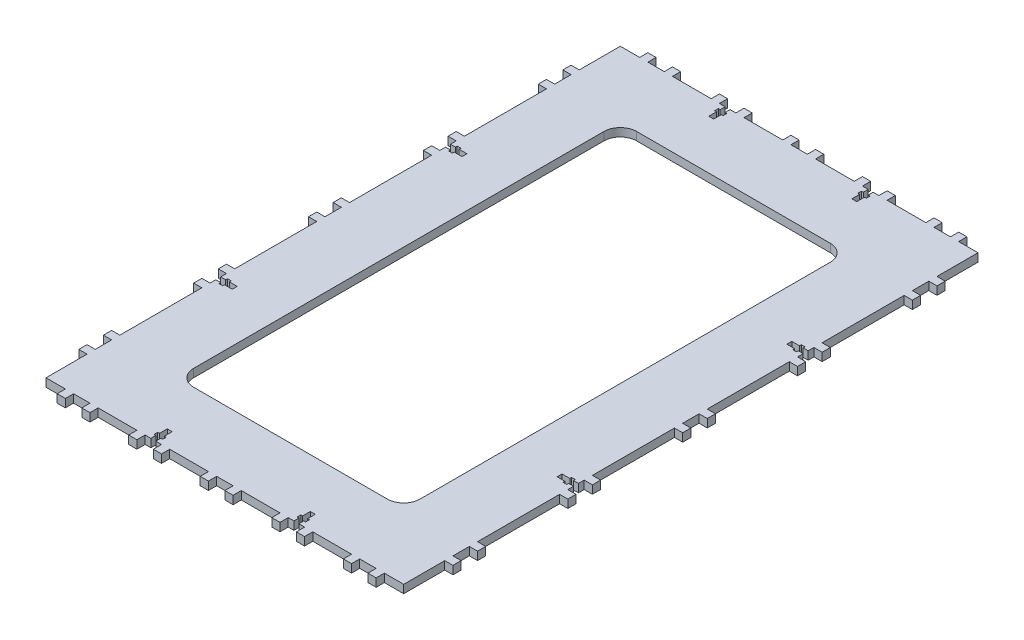
SolidWorks part; units mm, degrees
ref_plane "Front Plane" through (0, 0, 0) normal (0, 0, 1) x (1, 0, 0)
ref_plane "Top Plane" through (0, 0, 0) normal (0, 1, 0) x (1, 0, 0)
ref_plane "Right Plane" through (0, 0, 0) normal (1, 0, 0) x (0, 0, -1)
sketch "Sketch1" plane through (0, 0, 0) normal (0, 1, 0) x (1, 0, 0)
  line L0 (0, 0) -> (0, 175) construction
  line L64 (82.2, -175) -> (92.2, -175)
  line L87 (59, -135) -> (-59, -135)
  line L88 (69, -125) -> (69, 125)
  line L94 (109, -175) -> (109, -150)
  line L96 (-109, -175) -> (-97.2, -175)
  line L97 (-109, -175) -> (-109, -150)
  line L100 (59, 135) -> (-59, 135)
  line L118 (-109, -175) -> (109, 175) construction
  line L119 (-109, 175) -> (109, -175) construction
  line L121 (-109, 175) -> (-97.2, 175)
  line L122 (0, 0) -> (0, -206.09) construction
  line L123 (0, 0) -> (179.3861, 0) construction
  line L124 (0, -175) -> (0, -163.7792) construction
  line L125 (-1.5, -175) -> (-5, -175)
  line L126 (-5, -180) -> (-10, -180)
  line L127 (-10, -180) -> (-10, -175)
  line L128 (-5, -180) -> (-5, -175)
  line L145 (1.5, -175) -> (5, -175)
  line L146 (5, -175) -> (5, -180)
  line L147 (5, -180) -> (10, -180)
  line L148 (10, -180) -> (10, -175)
  line L149 (43.6, -175) -> (43.6, -177.9498) construction
  line L150 (42.1, -175) -> (38.6, -175)
  line L151 (38.6, -180) -> (33.6, -180)
  line L152 (33.6, -180) -> (33.6, -175)
  line L153 (38.6, -180) -> (38.6, -175)
  line L154 (45.1, -175) -> (48.6, -175)
  line L155 (48.6, -175) -> (48.6, -180)
  line L156 (48.6, -180) -> (53.6, -180)
  line L157 (53.6, -180) -> (53.6, -175)
  line L158 (87.2, -175) -> (87.2, -176.7176) construction
  line L159 (102.5, -175) -> (97.2, -175)
  line L160 (82.2, -180) -> (77.2, -180)
  line L161 (77.2, -180) -> (77.2, -175)
  line L162 (82.2, -180) -> (82.2, -175)
  line L163 (71.9, -175) -> (77.2, -175)
  line L164 (92.2, -175) -> (92.2, -180)
  line L165 (92.2, -180) -> (97.2, -180)
  line L166 (97.2, -180) -> (97.2, -175)
  line L167 (42.1, -175) -> (45.1, -175) construction
  line L168 (45.1, -175) -> (45.1, -172)
  line L169 (45.1, -169.7) -> (46.2, -169.7)
  line L170 (41, -172) -> (41, -169.7)
  line L171 (46.2, -172) -> (45.1, -172)
  line L172 (45.1, -169.7) -> (45.1, -165)
  line L173 (45.1, -165) -> (42.1, -165)
  line L174 (42.1, -165) -> (42.1, -169.7)
  line L175 (42.1, -172) -> (41, -172)
  line L176 (46.2, -169.7) -> (46.2, -172)
  line L177 (41, -169.7) -> (42.1, -169.7)
  line L178 (42.1, -172) -> (42.1, -175)
  line L179 (43.6, -165) -> (43.6, -175) construction
  line L180 (-1.5, -175) -> (1.5, -175) construction
  line L181 (109, -140) -> (144.5683, -140) construction
  line L182 (109, -141.5) -> (109, -145)
  line L183 (114, -145) -> (114, -150)
  line L184 (114, -150) -> (109, -150)
  line L185 (114, -145) -> (109, -145)
  line L186 (109, -138.5) -> (109, -135)
  line L187 (109, -135) -> (114, -135)
  line L188 (114, -135) -> (114, -130)
  line L189 (114, -130) -> (109, -130)
  line L190 (109, -141.5) -> (109, -138.5) construction
  line L191 (109, -130) -> (109, -80)
  line L192 (0, -165) -> (0, -175) construction
  line L193 (102.5, -175) -> (97.2, -175) construction
  line L194 (109, -145) -> (109, -135)
  line L195 (109, 10) -> (109, 60)
  line L196 (109, -5) -> (109, 5)
  line L197 (109, -60) -> (109, -10)
  line L198 (109, -75) -> (109, -65)
  line L199 (82.2, -175) -> (92.2, -175)
  line L200 (97.2, -175) -> (109, -175)
  line L201 (38.6, -175) -> (48.6, -175)
  line L202 (53.6, -175) -> (77.2, -175)
  line L203 (-5, -175) -> (5, -175)
  line L204 (10, -175) -> (33.6, -175)
  line L205 (87.2, -165) -> (87.2, -175) construction
  line L206 (109, -70) -> (138.8281, -70) construction
  line L207 (109, -71.5) -> (109, -75)
  line L208 (114, -75) -> (114, -80)
  line L209 (114, -80) -> (109, -80)
  line L210 (114, -75) -> (109, -75)
  line L211 (109, -68.5) -> (109, -65)
  line L212 (109, -65) -> (114, -65)
  line L213 (114, -65) -> (114, -60)
  line L214 (114, -60) -> (109, -60)
  line L215 (109, -71.5) -> (109, -68.5) construction
  line L216 (109, -68.5) -> (106, -68.5)
  line L217 (103.7, -68.5) -> (103.7, -67.4)
  line L218 (106, -72.6) -> (103.7, -72.6)
  line L219 (106, -67.4) -> (106, -68.5)
  line L220 (103.7, -68.5) -> (99, -68.5)
  line L221 (99, -68.5) -> (99, -71.5)
  line L222 (99, -71.5) -> (103.7, -71.5)
  line L223 (106, -71.5) -> (106, -72.6)
  line L224 (103.7, -67.4) -> (106, -67.4)
  line L225 (103.7, -72.6) -> (103.7, -71.5)
  line L226 (106, -71.5) -> (109, -71.5)
  line L227 (99, -70) -> (109, -70) construction
  line L228 (109, 0) -> (144.5683, 0) construction
  line L229 (109, -1.5) -> (109, -5)
  line L230 (114, -5) -> (114, -10)
  line L231 (114, -10) -> (109, -10)
  line L232 (114, -5) -> (109, -5)
  line L233 (109, 1.5) -> (109, 5)
  line L234 (109, 5) -> (114, 5)
  line L235 (114, 5) -> (114, 10)
  line L236 (114, 10) -> (109, 10)
  line L237 (109, -1.5) -> (109, 1.5) construction
  line L238 (99, 70) -> (109, 70) construction
  line L239 (109, 71.5) -> (109, 68.5) construction
  line L240 (109, 70) -> (138.8281, 70) construction
  line L241 (109, 141.5) -> (109, 138.5) construction
  line L242 (109, 140) -> (144.5683, 140) construction
  line L243 (106, 71.5) -> (109, 71.5)
  line L244 (103.7, 72.6) -> (103.7, 71.5)
  line L245 (103.7, 67.4) -> (106, 67.4)
  line L246 (106, 71.5) -> (106, 72.6)
  line L247 (99, 71.5) -> (103.7, 71.5)
  line L248 (99, 68.5) -> (99, 71.5)
  line L249 (120, 0) -> (109, 0) construction
  line L250 (103.7, 68.5) -> (99, 68.5)
  line L251 (106, 67.4) -> (106, 68.5)
  line L252 (106, 72.6) -> (103.7, 72.6)
  line L253 (103.7, 68.5) -> (103.7, 67.4)
  line L254 (109, 68.5) -> (106, 68.5)
  line L255 (114, 60) -> (109, 60)
  line L256 (114, 65) -> (114, 60)
  line L257 (109, 65) -> (114, 65)
  line L258 (109, 68.5) -> (109, 65)
  line L259 (114, 75) -> (109, 75)
  line L260 (114, 80) -> (109, 80)
  line L261 (114, 75) -> (114, 80)
  line L262 (109, 71.5) -> (109, 75)
  line L263 (109, 75) -> (109, 65)
  line L264 (109, 145) -> (109, 135)
  line L265 (114, 130) -> (109, 130)
  line L266 (114, 135) -> (114, 130)
  line L267 (109, 135) -> (114, 135)
  line L268 (109, 138.5) -> (109, 135)
  line L269 (114, 145) -> (109, 145)
  line L270 (114, 150) -> (109, 150)
  line L271 (114, 145) -> (114, 150)
  line L272 (109, 141.5) -> (109, 145)
  line L273 (-120, 0) -> (-109, 0) construction
  line L274 (-109, 140) -> (-144.5683, 140) construction
  line L275 (-109, 141.5) -> (-109, 138.5) construction
  line L276 (-109, 70) -> (-138.8281, 70) construction
  line L277 (-109, 71.5) -> (-109, 68.5) construction
  line L278 (-99, 70) -> (-109, 70) construction
  line L279 (-109, -1.5) -> (-109, 1.5) construction
  line L280 (-109, 0) -> (-144.5683, 0) construction
  line L281 (-99, -70) -> (-109, -70) construction
  line L282 (-109, -71.5) -> (-109, -68.5) construction
  line L283 (-109, -70) -> (-138.8281, -70) construction
  line L284 (-109, -141.5) -> (-109, -138.5) construction
  line L285 (-109, -140) -> (-144.5683, -140) construction
  line L286 (-109, 141.5) -> (-109, 145)
  line L287 (-114, 145) -> (-114, 150)
  line L288 (-114, 150) -> (-109, 150)
  line L289 (-114, 145) -> (-109, 145)
  line L290 (-109, 138.5) -> (-109, 135)
  line L291 (-109, 135) -> (-114, 135)
  line L292 (-114, 135) -> (-114, 130)
  line L293 (-114, 130) -> (-109, 130)
  line L294 (-109, 145) -> (-109, 135)
  line L295 (-109, 75) -> (-109, 65)
  line L296 (-109, 71.5) -> (-109, 75)
  line L297 (-114, 75) -> (-114, 80)
  line L298 (-114, 80) -> (-109, 80)
  line L299 (-114, 75) -> (-109, 75)
  line L300 (-109, 68.5) -> (-109, 65)
  line L301 (-109, 65) -> (-114, 65)
  line L302 (-114, 65) -> (-114, 60)
  line L303 (-114, 60) -> (-109, 60)
  line L304 (-109, 68.5) -> (-106, 68.5)
  line L305 (-103.7, 68.5) -> (-103.7, 67.4)
  line L306 (-106, 72.6) -> (-103.7, 72.6)
  line L307 (-106, 67.4) -> (-106, 68.5)
  line L308 (-103.7, 68.5) -> (-99, 68.5)
  line L309 (-99, 68.5) -> (-99, 71.5)
  line L310 (-99, 71.5) -> (-103.7, 71.5)
  line L311 (-106, 71.5) -> (-106, 72.6)
  line L312 (-103.7, 67.4) -> (-106, 67.4)
  line L313 (-103.7, 72.6) -> (-103.7, 71.5)
  line L314 (-106, 71.5) -> (-109, 71.5)
  line L315 (-114, 10) -> (-109, 10)
  line L316 (-114, 5) -> (-114, 10)
  line L317 (-109, 5) -> (-114, 5)
  line L318 (-109, 1.5) -> (-109, 5)
  line L319 (-114, -5) -> (-109, -5)
  line L320 (-114, -10) -> (-109, -10)
  line L321 (-114, -5) -> (-114, -10)
  line L322 (-109, -1.5) -> (-109, -5)
  line L323 (-106, -71.5) -> (-109, -71.5)
  line L324 (-103.7, -72.6) -> (-103.7, -71.5)
  line L325 (-103.7, -67.4) -> (-106, -67.4)
  line L326 (-106, -71.5) -> (-106, -72.6)
  line L327 (-99, -71.5) -> (-103.7, -71.5)
  line L328 (-99, -68.5) -> (-99, -71.5)
  line L329 (-103.7, -68.5) -> (-99, -68.5)
  line L330 (-106, -67.4) -> (-106, -68.5)
  line L331 (-106, -72.6) -> (-103.7, -72.6)
  line L332 (-103.7, -68.5) -> (-103.7, -67.4)
  line L333 (-109, -68.5) -> (-106, -68.5)
  line L334 (-114, -60) -> (-109, -60)
  line L335 (-114, -65) -> (-114, -60)
  line L336 (-109, -65) -> (-114, -65)
  line L337 (-109, -68.5) -> (-109, -65)
  line L338 (-114, -75) -> (-109, -75)
  line L339 (-114, -80) -> (-109, -80)
  line L340 (-114, -75) -> (-114, -80)
  line L341 (-109, -71.5) -> (-109, -75)
  line L342 (-109, -75) -> (-109, -65)
  line L343 (-109, -5) -> (-109, 5)
  line L344 (-109, -145) -> (-109, -135)
  line L345 (-114, -130) -> (-109, -130)
  line L346 (-114, -135) -> (-114, -130)
  line L347 (-109, -135) -> (-114, -135)
  line L348 (-109, -138.5) -> (-109, -135)
  line L349 (-114, -145) -> (-109, -145)
  line L350 (-114, -150) -> (-109, -150)
  line L351 (-114, -145) -> (-114, -150)
  line L352 (-109, -141.5) -> (-109, -145)
  line L353 (-87.2, -165) -> (-87.2, -175) construction
  line L354 (-102.5, -175) -> (-97.2, -175) construction
  line L355 (-43.6, -165) -> (-43.6, -175) construction
  line L356 (-87.2, -175) -> (-87.2, -176.7176) construction
  line L357 (-42.1, -175) -> (-45.1, -175) construction
  line L358 (-53.6, -175) -> (-77.2, -175)
  line L359 (-43.6, -175) -> (-43.6, -177.9498) construction
  line L360 (-82.2, -175) -> (-92.2, -175)
  line L361 (-38.6, -175) -> (-48.6, -175)
  line L362 (-42.1, -172) -> (-42.1, -175)
  line L363 (-41, -169.7) -> (-42.1, -169.7)
  line L364 (-46.2, -169.7) -> (-46.2, -172)
  line L365 (-42.1, -172) -> (-41, -172)
  line L366 (-42.1, -165) -> (-42.1, -169.7)
  line L367 (-97.2, -180) -> (-97.2, -175)
  line L368 (-92.2, -180) -> (-97.2, -180)
  line L369 (-92.2, -175) -> (-92.2, -180)
  line L370 (-71.9, -175) -> (-77.2, -175)
  line L371 (-82.2, -180) -> (-82.2, -175)
  line L372 (-77.2, -180) -> (-77.2, -175)
  line L373 (-82.2, -180) -> (-77.2, -180)
  line L374 (-102.5, -175) -> (-97.2, -175)
  line L375 (-45.1, -165) -> (-42.1, -165)
  line L376 (-45.1, -169.7) -> (-45.1, -165)
  line L377 (-46.2, -172) -> (-45.1, -172)
  line L378 (-41, -172) -> (-41, -169.7)
  line L379 (-45.1, -169.7) -> (-46.2, -169.7)
  line L380 (-45.1, -175) -> (-45.1, -172)
  line L381 (-53.6, -180) -> (-53.6, -175)
  line L382 (-48.6, -180) -> (-53.6, -180)
  line L383 (-48.6, -175) -> (-48.6, -180)
  line L384 (-45.1, -175) -> (-48.6, -175)
  line L385 (-38.6, -180) -> (-38.6, -175)
  line L386 (-33.6, -180) -> (-33.6, -175)
  line L387 (-38.6, -180) -> (-33.6, -180)
  line L388 (-42.1, -175) -> (-38.6, -175)
  line L389 (-43.6, 175) -> (-43.6, 177.9498) construction
  line L390 (-42.1, 175) -> (-45.1, 175) construction
  line L391 (-87.2, 175) -> (-87.2, 176.7176) construction
  line L392 (-43.6, 165) -> (-43.6, 175) construction
  line L393 (-102.5, 175) -> (-97.2, 175) construction
  line L394 (-87.2, 165) -> (-87.2, 175) construction
  line L395 (87.2, 165) -> (87.2, 175) construction
  line L396 (102.5, 175) -> (97.2, 175) construction
  line L397 (0, 165) -> (0, 175) construction
  line L398 (-1.5, 175) -> (1.5, 175) construction
  line L399 (43.6, 165) -> (43.6, 175) construction
  line L400 (42.1, 175) -> (45.1, 175) construction
  line L401 (87.2, 175) -> (87.2, 176.7176) construction
  line L402 (43.6, 175) -> (43.6, 177.9498) construction
  line L403 (0, 175) -> (0, 163.7792) construction
  line L404 (-42.1, 175) -> (-38.6, 175)
  line L405 (-38.6, 180) -> (-33.6, 180)
  line L406 (-33.6, 180) -> (-33.6, 175)
  line L407 (-38.6, 180) -> (-38.6, 175)
  line L408 (-45.1, 175) -> (-48.6, 175)
  line L409 (-48.6, 175) -> (-48.6, 180)
  line L410 (-48.6, 180) -> (-53.6, 180)
  line L411 (-53.6, 180) -> (-53.6, 175)
  line L412 (-45.1, 175) -> (-45.1, 172)
  line L413 (-45.1, 169.7) -> (-46.2, 169.7)
  line L414 (-41, 172) -> (-41, 169.7)
  line L415 (-46.2, 172) -> (-45.1, 172)
  line L416 (-45.1, 169.7) -> (-45.1, 165)
  line L417 (-45.1, 165) -> (-42.1, 165)
  line L418 (-102.5, 175) -> (-97.2, 175)
  line L419 (-82.2, 180) -> (-77.2, 180)
  line L420 (-77.2, 180) -> (-77.2, 175)
  line L421 (-82.2, 180) -> (-82.2, 175)
  line L422 (-71.9, 175) -> (-77.2, 175)
  line L423 (-92.2, 175) -> (-92.2, 180)
  line L424 (-92.2, 180) -> (-97.2, 180)
  line L425 (-97.2, 180) -> (-97.2, 175)
  line L426 (-42.1, 165) -> (-42.1, 169.7)
  line L427 (-42.1, 172) -> (-41, 172)
  line L428 (-46.2, 169.7) -> (-46.2, 172)
  line L429 (-41, 169.7) -> (-42.1, 169.7)
  line L430 (-42.1, 172) -> (-42.1, 175)
  line L431 (-38.6, 175) -> (-48.6, 175)
  line L432 (-82.2, 175) -> (-92.2, 175)
  line L433 (-53.6, 175) -> (-77.2, 175)
  line L434 (10, 175) -> (33.6, 175)
  line L435 (-5, 175) -> (5, 175)
  line L436 (53.6, 175) -> (77.2, 175)
  line L437 (38.6, 175) -> (48.6, 175)
  line L438 (82.2, 175) -> (92.2, 175)
  line L439 (42.1, 172) -> (42.1, 175)
  line L440 (41, 169.7) -> (42.1, 169.7)
  line L441 (46.2, 169.7) -> (46.2, 172)
  line L442 (42.1, 172) -> (41, 172)
  line L443 (42.1, 165) -> (42.1, 169.7)
  line L444 (45.1, 165) -> (42.1, 165)
  line L445 (45.1, 169.7) -> (45.1, 165)
  line L446 (46.2, 172) -> (45.1, 172)
  line L447 (41, 172) -> (41, 169.7)
  line L448 (45.1, 169.7) -> (46.2, 169.7)
  line L449 (45.1, 175) -> (45.1, 172)
  line L450 (97.2, 180) -> (97.2, 175)
  line L451 (92.2, 180) -> (97.2, 180)
  line L452 (92.2, 175) -> (92.2, 180)
  line L453 (71.9, 175) -> (77.2, 175)
  line L454 (82.2, 180) -> (82.2, 175)
  line L455 (77.2, 180) -> (77.2, 175)
  line L456 (82.2, 180) -> (77.2, 180)
  line L457 (102.5, 175) -> (97.2, 175)
  line L458 (53.6, 180) -> (53.6, 175)
  line L459 (48.6, 180) -> (53.6, 180)
  line L460 (48.6, 175) -> (48.6, 180)
  line L461 (45.1, 175) -> (48.6, 175)
  line L462 (38.6, 180) -> (38.6, 175)
  line L463 (33.6, 180) -> (33.6, 175)
  line L464 (38.6, 180) -> (33.6, 180)
  line L465 (42.1, 175) -> (38.6, 175)
  line L466 (10, 180) -> (10, 175)
  line L467 (5, 180) -> (10, 180)
  line L468 (5, 175) -> (5, 180)
  line L469 (1.5, 175) -> (5, 175)
  line L470 (-5, 180) -> (-5, 175)
  line L471 (-10, 180) -> (-10, 175)
  line L472 (-5, 180) -> (-10, 180)
  line L473 (-1.5, 175) -> (-5, 175)
  line L474 (-92.2, 175) -> (-82.2, 175)
  line L475 (-77.2, 175) -> (-53.6, 175)
  line L476 (-48.6, 175) -> (-38.6, 175)
  line L477 (-33.6, 175) -> (-10, 175)
  line L478 (-5, 175) -> (5, 175)
  line L479 (10, 175) -> (33.6, 175)
  line L480 (38.6, 175) -> (48.6, 175)
  line L481 (53.6, 175) -> (77.2, 175)
  line L482 (82.2, 175) -> (92.2, 175)
  line L483 (97.2, 175) -> (109, 175)
  line L484 (-109, 150) -> (-109, 175)
  line L485 (-109, 135) -> (-109, 145)
  line L486 (-109, 80) -> (-109, 130)
  line L487 (-109, 65) -> (-109, 75)
  line L488 (-109, 10) -> (-109, 60)
  line L489 (-109, -5) -> (-109, 5)
  line L490 (-109, -60) -> (-109, -10)
  line L491 (-109, -75) -> (-109, -65)
  line L492 (-109, -130) -> (-109, -80)
  line L493 (-109, -145) -> (-109, -135)
  line L494 (-92.2, -175) -> (-82.2, -175)
  line L495 (-77.2, -175) -> (-53.6, -175)
  line L496 (-48.6, -175) -> (-38.6, -175)
  line L497 (-33.6, -175) -> (-10, -175)
  line L498 (109, 150) -> (109, 175)
  line L499 (109, 135) -> (109, 145)
  line L500 (109, 80) -> (109, 130)
  line L501 (109, 65) -> (109, 75)
  line L502 (-69, -125) -> (-69, 125)
  line L503 (69, -135) -> (-69, 135) construction
  line L504 (69, 135) -> (-69, -135) construction
  line L505 (77.2, -175) -> (71.9, -175) construction
  line L506 (92.2, -175) -> (82.2, -175)
  line L507 (92.2, -175) -> (82.2, -175) construction
  line L508 (-92.2, -175) -> (-82.2, -175) construction
  line L509 (-92.2, -175) -> (-82.2, -175)
  line L510 (-82.2, -175) -> (-92.2, -175)
  line L511 (-77.2, -175) -> (-71.9, -175) construction
  line L512 (92.2, 175) -> (82.2, 175) construction
  line L513 (92.2, 175) -> (82.2, 175)
  line L514 (82.2, 175) -> (92.2, 175)
  line L515 (77.2, 175) -> (71.9, 175) construction
  line L516 (-92.2, 175) -> (-82.2, 175) construction
  line L517 (-92.2, 175) -> (-82.2, 175)
  line L518 (-82.2, 175) -> (-92.2, 175)
  line L519 (-77.2, 175) -> (-71.9, 175) construction
  arc A0 (-59, -135) -> (-69, -125) centre (-59, -125) cw
  arc A1 (69, -125) -> (59, -135) centre (59, -125) cw
  arc A2 (69, 125) -> (59, 135) centre (59, 125) ccw
  arc A3 (-59, 135) -> (-69, 125) centre (-59, 125) ccw
  dimension "D23" = 10
  dimension "D24" = 5
  dimension "D10" = 10
  dimension "D1" = 40
  dimension "D4" = 350
  dimension "D5" = 218
  dimension "D6" = 10
  dimension "D7" = 5
  dimension "D8" = 5
  dimension "D9" = 40
  dimension "D25" = 5
  dimension "D26" = 10
  dimension "D27" = 5
  dimension "D28" = 5
  dimension "D29" = 5.2
  dimension "D30" = 3
  dimension "D31" = 2.3
  dimension "D32" = 3
  dimension "D33" = 10
  dimension "D34" = 43.6
  dimension "D35" = 43.6
  dimension "D36" = 10
  dimension "D37" = 5
  dimension "D38" = 5
  dimension "D44" = 10
  dimension "D45" = 5
  dimension "D46" = 5
  dimension "D47" = 5.2
  dimension "D48" = 3
  dimension "D49" = 2.3
  dimension "D50" = 3
  dimension "D51" = 10
  dimension "D52" = 10
  dimension "D53" = 5
  dimension "D54" = 5
  dimension "D61" = 70
extrude "Boss-Extrude1" add sketch "Sketch1" along normal blind 5 contours L260 L500 L265 L266 L267 L264 L269 L271 L270 L498 L483 L450 L451 L452 L438 L454 L456 L455 L436 L458 L459 L460 L437 L449 L446 L441 L448 L445 L444 L443 L440 L447 L442 L439 L462 L464 L463 L434 L466 L467 L468 L435 L470 L472
